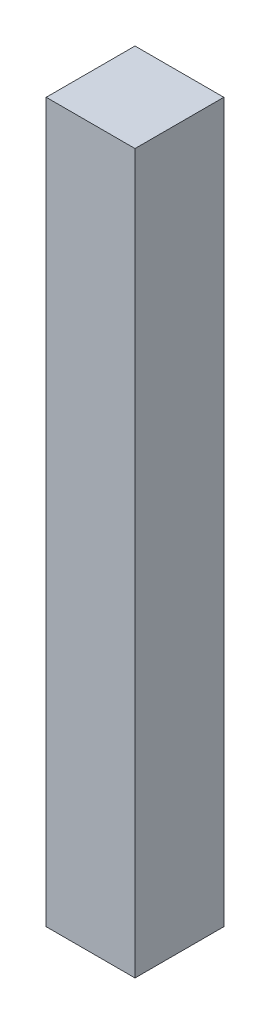
SolidWorks part; units mm, degrees
ref_plane "Front Plane" through (0, 0, 0) normal (0, 0, 1) x (1, 0, 0)
ref_plane "Top Plane" through (0, 0, 0) normal (0, 1, 0) x (1, 0, 0)
ref_plane "Right Plane" through (0, 0, 0) normal (1, 0, 0) x (0, 0, -1)
sketch "Sketch1" plane through (0, 0, 0) normal (0, 1, 0) x (1, 0, 0)
  line L1 (0, 0) -> (20, 0)
  line L2 (0, 0) -> (0, -20)
  line L3 (0, -20) -> (20, -20)
  line L4 (20, 0) -> (20, -20)
extrude "Boss-Extrude1" add sketch "Sketch1" along normal up to surface (161.7913 mm away)
